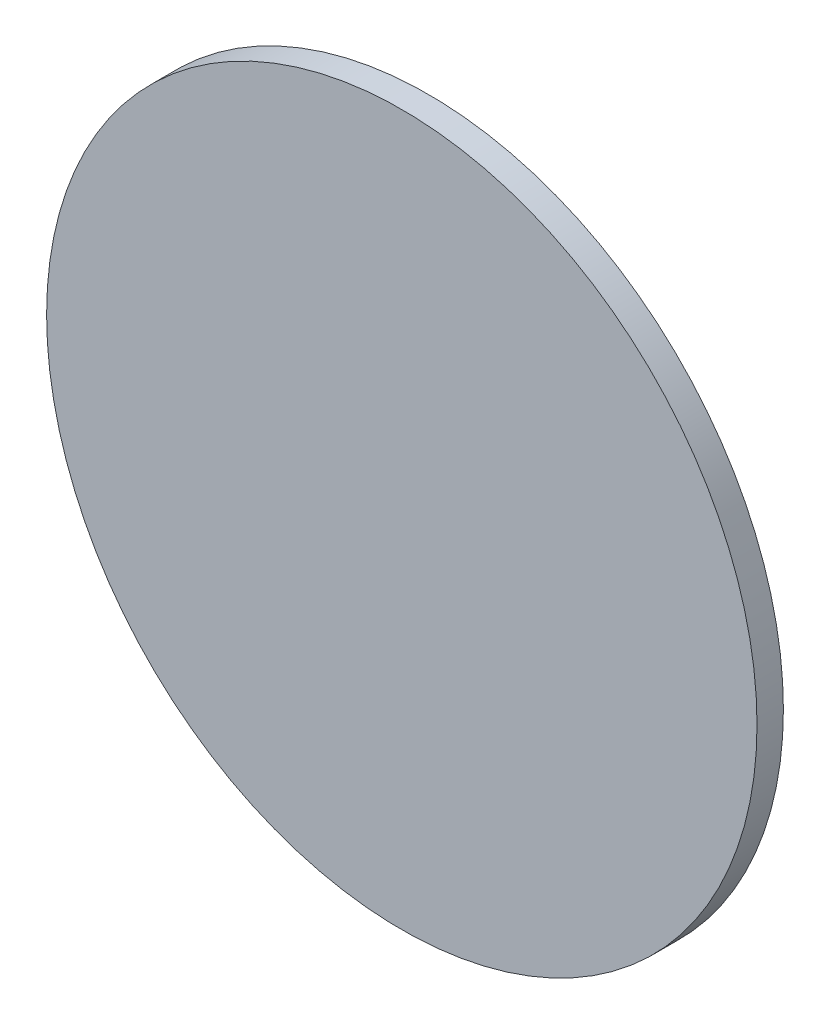
SolidWorks part; units mm, degrees
material "PMMA"
ref_plane "前视基准面" through (0, 0, 0) normal (0, 0, 1) x (1, 0, 0)
ref_plane "上视基准面" through (0, 0, 0) normal (0, 1, 0) x (1, 0, 0)
ref_plane "右视基准面" through (0, 0, 0) normal (1, 0, 0) x (0, 0, -1)
other "Configuration Table"
sketch "草图1" plane through (0, 0, 0) normal (0, 0, 1) x (1, 0, 0)
  circle A0 centre (0, 0) radius 20.2
extrude "凸台-拉伸1" add sketch "草图1" along normal blind 1.5
